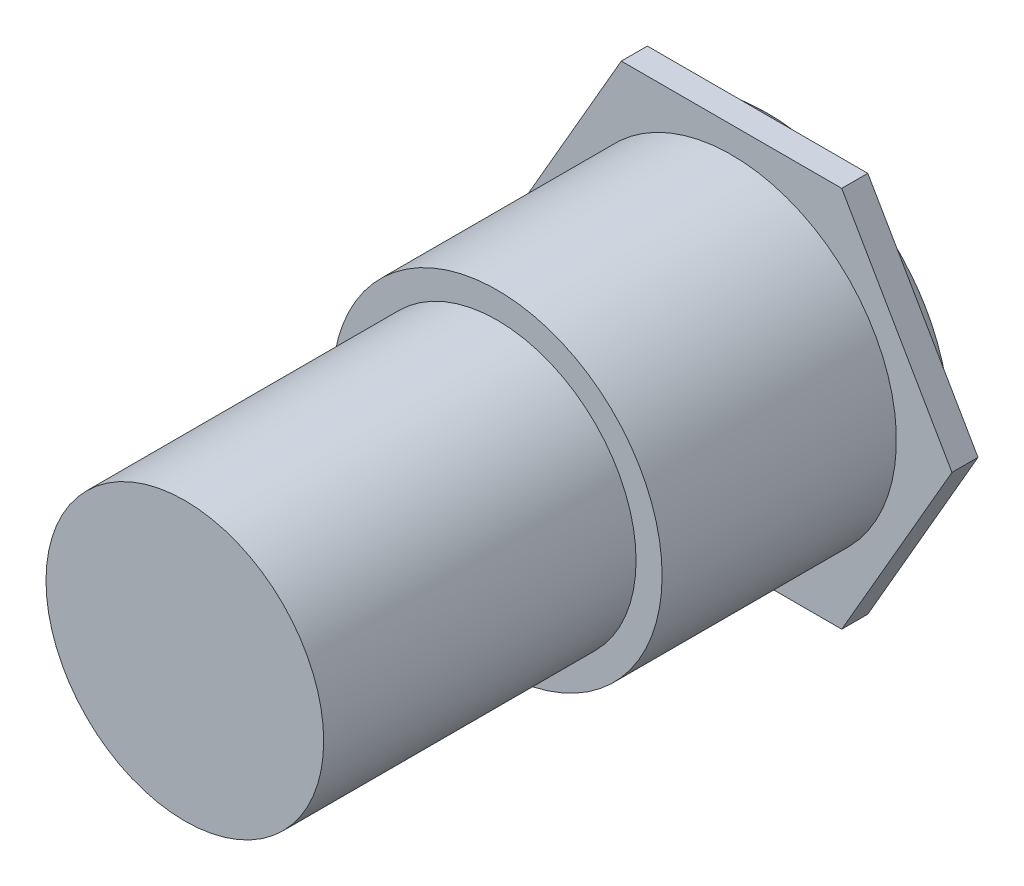
SolidWorks part; units mm, degrees
ref_plane "前视基准面" through (0, 0, 0) normal (0, 0, 1) x (1, 0, 0)
ref_plane "上视基准面" through (0, 0, 0) normal (0, 1, 0) x (1, 0, 0)
ref_plane "右视基准面" through (0, 0, 0) normal (1, 0, 0) x (0, 0, -1)
sketch "草图1" plane through (0, 0, 0) normal (0, 0, 1) x (1, 0, 0)
  circle A0 centre (0, 0) radius 9.5
  dimension "D1" = 19
extrude "凸台-拉伸1" add sketch "草图1" along normal blind 15
sketch "草图2" plane through (0, 0, 0) normal (0, 0, -1) x (-1, 0, 0)
  line L1 (6.3509, 11) -> (-6.3509, 11)
  line L2 (-6.3509, 11) -> (-12.7017, 0)
  line L3 (-12.7017, 0) -> (-6.3509, -11)
  line L4 (-6.3509, -11) -> (6.3509, -11)
  line L5 (6.3509, -11) -> (12.7017, 0)
  line L6 (12.7017, 0) -> (6.3509, 11)
  circle A0 centre (0, 0) radius 11 construction
  dimension "D1" = 22
extrude "凸台-拉伸2" add sketch "草图2" against normal blind 1.5
sketch "草图3" plane through (0, 0, 0) normal (0, 1, 0) x (1, 0, 0)
  line L0 (0, 0) -> (0, 1.5)
  line L1 (0, 1.5) -> (-8.5, 1.5)
  line L2 (0, 0) -> (-11, 0)
  line L3 (-12.7017, 0) -> (-6.3509, 0) construction
  arc A0 (-11, 0) -> (-8.5, 1.5) centre (-8.2268, -1.7887) cw
  point P4 (-9.4288, 1.5)
  dimension "D3" = 3.3
  dimension "D1" = 11
  dimension "D2" = 1.5
  dimension "D4" = 8.5
revolve "旋转1" add sketch "草图3" angle 360 about L0
sketch "草图4" plane through (0, 0, 15) normal (0, 0, 1) x (1, 0, 0)
  circle A0 centre (0, 0) radius 8
  dimension "D1" = 16
extrude "凸台-拉伸3" add sketch "草图4" along normal blind 18
